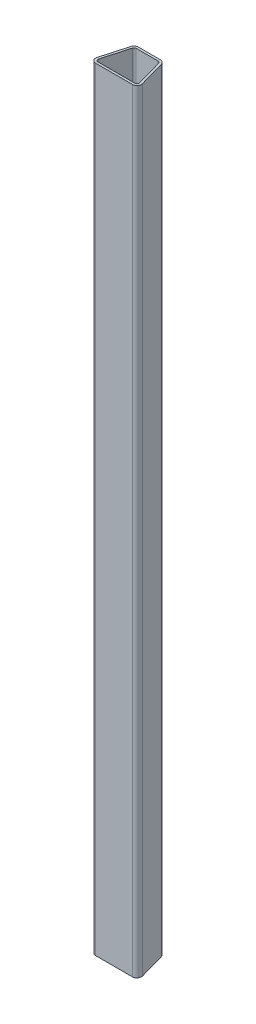
SolidWorks part; units mm, degrees
ref_plane "Front Plane" through (0, 0, 0) normal (0, 0, 1) x (1, 0, 0)
ref_plane "Top Plane" through (0, 0, 0) normal (0, 1, 0) x (1, 0, 0)
ref_plane "Right Plane" through (0, 0, 0) normal (1, 0, 0) x (0, 0, -1)
sketch "Sketch1" plane through (0, 0, 0) normal (0, 1, 0) x (1, 0, 0)
  line L0 (-8.3599, -8) -> (8.3599, -8)
  line L1 (-8.3599, -7) -> (8.3599, -7)
  line L2 (-4.9849, 8) -> (4.9849, 8)
  line L3 (-6.9102, 6.5415) -> (-10.2852, -5.4585)
  line L4 (6.9102, 6.5415) -> (10.2852, -5.4585)
  line L5 (5.9476, 6.2707) -> (9.3226, -5.7293)
  line L6 (-4.9849, 7) -> (4.9849, 7)
  line L7 (-5.9476, 6.2707) -> (-9.3226, -5.7293)
  arc A0 (8.3599, -8) -> (10.2852, -5.4585) centre (8.3599, -6) ccw
  arc A1 (-8.3599, -8) -> (-10.2852, -5.4585) centre (-8.3599, -6) cw
  arc A2 (-4.9849, 8) -> (-6.9102, 6.5415) centre (-4.9849, 6) ccw
  arc A3 (4.9849, 8) -> (6.9102, 6.5415) centre (4.9849, 6) cw
  arc A4 (8.3599, -7) -> (9.3226, -5.7293) centre (8.3599, -6) ccw
  arc A5 (4.9849, 7) -> (5.9476, 6.2707) centre (4.9849, 6) cw
  arc A6 (-4.9849, 7) -> (-5.9476, 6.2707) centre (-4.9849, 6) ccw
  arc A7 (-8.3599, -7) -> (-9.3226, -5.7293) centre (-8.3599, -6) cw
  point P11 (11, -8)
  point P14 (-11, -8)
  point P17 (-6.5, 8)
  point P20 (6.5, 8)
  dimension "D4" = 2
  dimension "D1" = 22
  dimension "D2" = 1
  dimension "D3" = 13
extrude "Boss-Extrude1" add sketch "Sketch1" along normal blind 350
